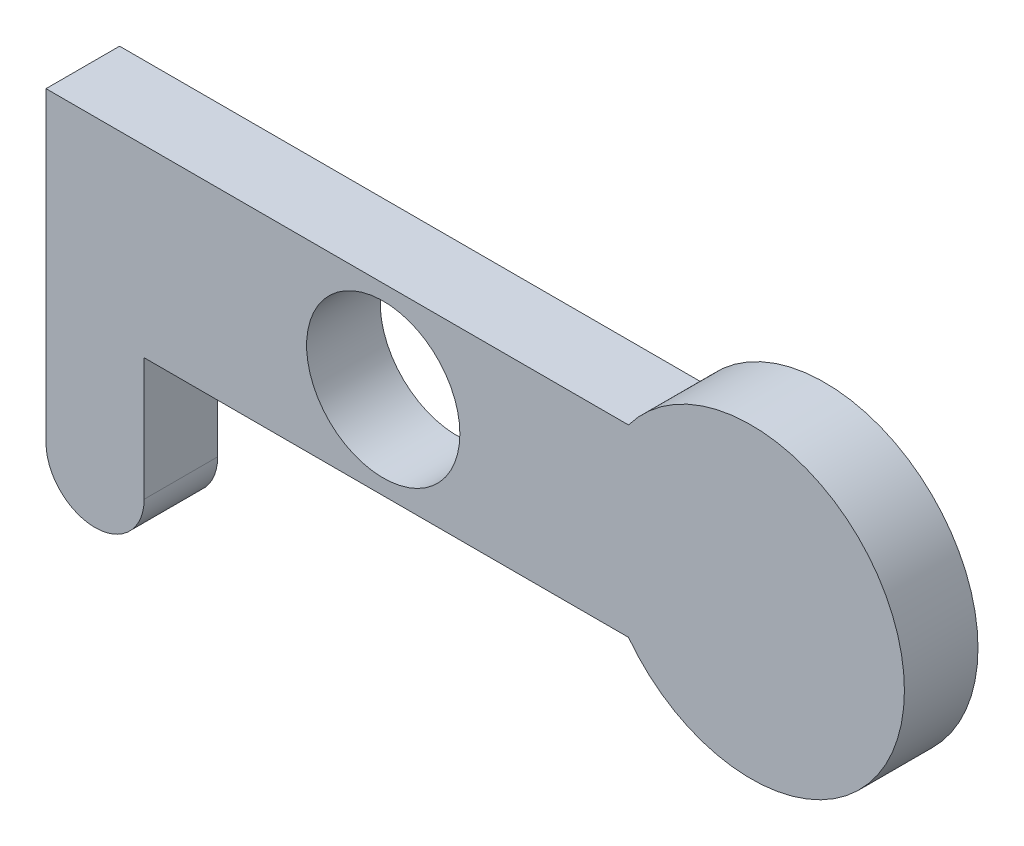
SolidWorks part; units mm, degrees
ref_plane "Piano frontale" through (0, 0, 0) normal (0, 0, 1) x (1, 0, 0)
ref_plane "Piano superiore" through (0, 0, 0) normal (0, 1, 0) x (1, 0, 0)
ref_plane "Piano destro" through (0, 0, 0) normal (1, 0, 0) x (0, 0, -1)
sketch "Schizzo1" plane through (0, 0, 0) normal (0, 0, 1) x (1, 0, 0)
  line L0 (0, 0) -> (-19.5, 0)
  line L1 (-19.5, 0) -> (-19.5, -10)
  line L2 (-27.5, -10) -> (-27.5, 15)
  line L3 (-27.5, 15) -> (8.0322, 15)
  line L4 (0, 0) -> (20, 0)
  line L5 (8.0322, 15) -> (20, 15)
  arc A0 (-19.5, -10) -> (-27.5, -10) centre (-23.5, -10) cw
  arc A1 (20, 0) -> (20, 15) centre (30, 7.5) ccw
  circle A2 centre (0, 7.5) radius 6.25
  dimension "D2" = 25
  dimension "D4" = 12.5
  dimension "D7" = 42.5
  dimension "D1" = 8
  dimension "D3" = 25
  dimension "D5" = 15
  dimension "D6" = 27.5
extrude "Estrusione-Estrusione1" add sketch "Schizzo1" along normal blind 6
